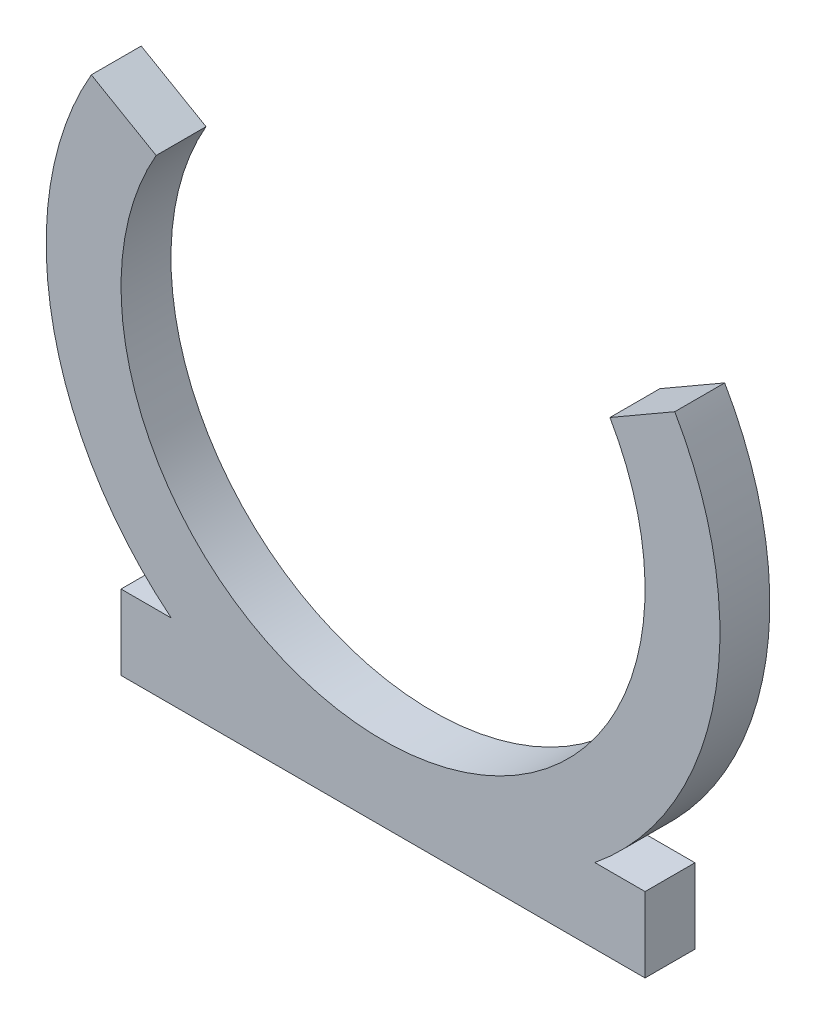
SolidWorks part; units mm, degrees
ref_plane "Front Plane" through (0, 0, 0) normal (0, 0, 1) x (1, 0, 0)
ref_plane "Top Plane" through (0, 0, 0) normal (0, 1, 0) x (1, 0, 0)
ref_plane "Right Plane" through (0, 0, 0) normal (1, 0, 0) x (0, 0, -1)
sketch "Sketch1" plane through (0, 0, 0) normal (0, 0, 1) x (1, 0, 0)
  line L0 (-9.0933, 5.25) -> (-11.6913, 6.75)
  line L1 (0, 0) -> (0, 14.2965) construction
  line L2 (9.0933, 5.25) -> (11.6913, 6.75)
  line L3 (0, -9.5544) -> (0, -16.694) construction
  line L4 (-10.5, -10.5) -> (-8.4853, -10.5)
  line L5 (-10.5, -10.5) -> (-10.5, -13.5)
  line L6 (-10.5, -13.5) -> (10.5, -13.5)
  line L7 (10.5, -10.5) -> (10.5, -13.5)
  line L8 (8.4853, -10.5) -> (10.5, -10.5)
  arc A0 (-9.0933, 5.25) -> (9.0933, 5.25) centre (0, 0) ccw
  arc A1 (-11.6913, 6.75) -> (-8.4853, -10.5) centre (0, 0) ccw
  arc A2 (8.4853, -10.5) -> (11.6913, 6.75) centre (0, 0) ccw
  circle A3 centre (0, 0) radius 10.5 construction
  circle A4 centre (0, 0) radius 13.5 construction
  point P5 (10.0412, 3.0699)
  point P10 (12.5, 0)
  dimension "D1" = 21
  dimension "D3" = 60
  dimension "D4" = 3
  dimension "D5" = 10.5
  dimension "D6" = 21
  dimension "D2" = 3
extrude "Boss-Extrude1" add sketch "Sketch1" along normal blind 2
